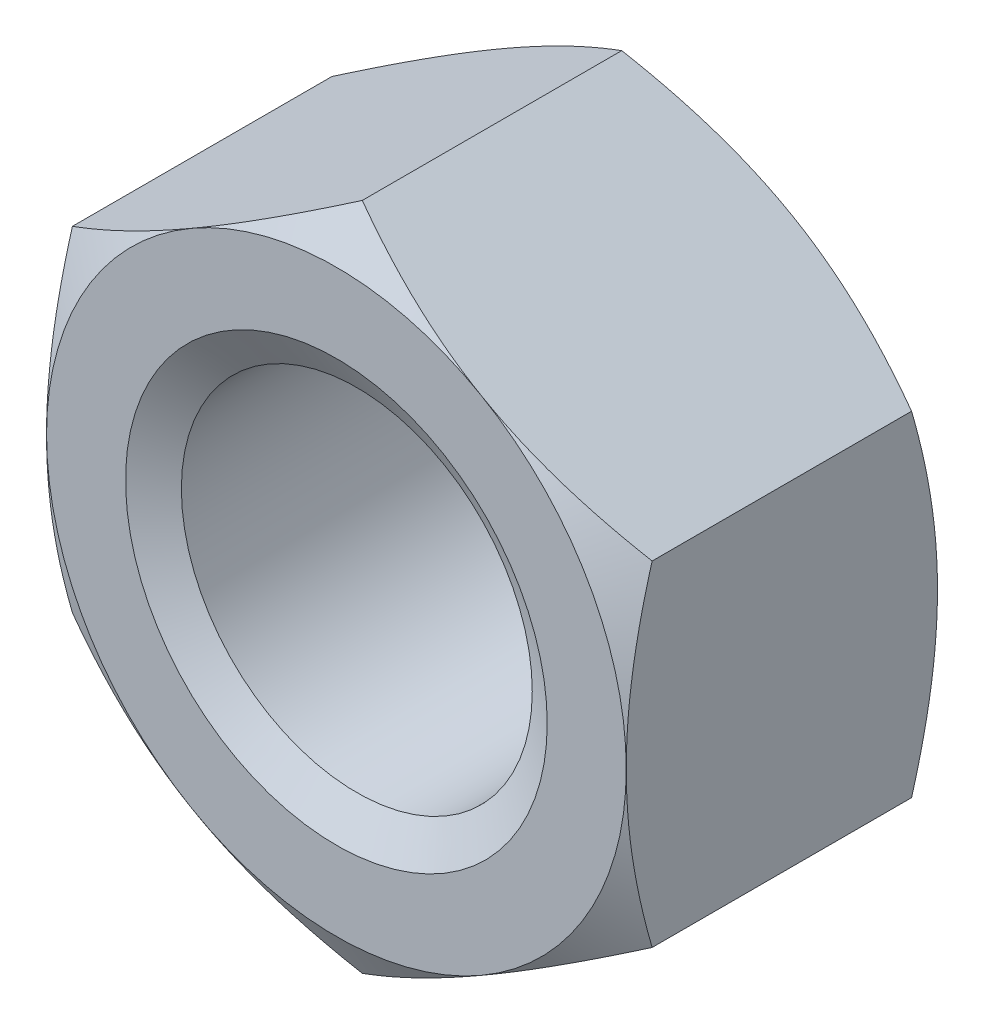
SolidWorks part; units mm, degrees
ref_plane "前视基准面" through (0, 0, 0) normal (0, 0, 1) x (1, 0, 0)
ref_plane "上视基准面" through (0, 0, 0) normal (0, 1, 0) x (1, 0, 0)
ref_plane "右视基准面" through (0, 0, 0) normal (1, 0, 0) x (0, 0, -1)
sketch "草图1" plane through (0, 0, 0) normal (1, 0, 0) x (0, 0, -1)
  line L0 (0, 52.43) -> (0, -52.43) construction
  line L1 (0, 0) -> (51, 0) construction
  line L2 (0, 0) -> (0, 52.43)
  line L3 (0, 52.43) -> (51, 52.43)
  line L4 (51, 52.43) -> (51, 0)
  line L5 (0, 32) -> (51, 32)
  line L6 (0, 28.7525) -> (51, 28.7525)
  line L7 (50, 52.43) -> (50, 0)
  line L8 (0, 47.5) -> (2.8463, 52.43)
  line L9 (0, 32) -> (1.8749, 28.7525)
  line L10 (0, -32) -> (1.8749, -28.7525)
  line L11 (50, 44.1) -> (51, 44.1)
  point P5 (11.7, 0)
  point P10 (45, 0)
  point P22 (0, 69.1)
  dimension "e" = 104.86
  dimension "m" = 51
  dimension "mw" = 39.3
  dimension "D" = 64
  dimension "P" = 6
  dimension "D81" = 57.505
  dimension "c" = 1
  dimension "β" = 30
  dimension "s" = 95
  dimension "θ" = 120
  dimension "dw" = 88.2
  dimension "da" = 69.1
sketch "草图2" plane through (0, 0, 0) normal (0, 0, 1) x (1, 0, 0)
  line L1 (0, 54.8483) -> (-47.5, 27.4241)
  line L2 (-47.5, 27.4241) -> (-47.5, -27.4241)
  line L3 (-47.5, -27.4241) -> (0, -54.8483)
  line L4 (0, -54.8483) -> (47.5, -27.4241)
  line L5 (47.5, -27.4241) -> (47.5, 27.4241)
  line L6 (47.5, 27.4241) -> (0, 54.8483)
  circle A0 centre (0, 0) radius 47.5 construction
  circle A1 centre (0, 0) radius 28.7525
  dimension "D1" = 95
sketch "草图3" plane through (0, 0, 0) normal (0, 0, 1) x (1, 0, 0)
  line L0 (0, 54.8483) -> (-47.5, 27.4241) construction
  line L1 (47.5, 27.4241) -> (0, 54.8483) construction
  line L2 (47.5, -27.4241) -> (47.5, 27.4241) construction
  line L3 (0, -54.8483) -> (47.5, -27.4241) construction
  line L4 (-47.5, -27.4241) -> (0, -54.8483) construction
  line L5 (-47.5, 27.4241) -> (-47.5, -27.4241) construction
  line L6 (0, 54.8483) -> (-47.5, 27.4241)
  line L7 (47.5, 27.4241) -> (0, 54.8483)
  line L8 (47.5, -27.4241) -> (47.5, 27.4241)
  line L9 (0, -54.8483) -> (47.5, -27.4241)
  line L10 (-47.5, -27.4241) -> (0, -54.8483)
  line L11 (-47.5, 27.4241) -> (-47.5, -27.4241)
  circle A0 centre (0, 0) radius 28.7525 construction
  circle A1 centre (0, 0) radius 28.7525
extrude "凸台-拉伸1" add sketch "草图3" against normal up to vertex (51 mm away) up to point (0, 0, -51)
cosmetic thread "装饰螺纹线1" parameters "D2"=64
sketch "草图4" plane through (0, 0, 0) normal (1, 0, 0) x (0, 0, -1)
  line L1 (0, 34.55) -> (3.3472, 28.7525)
  line L2 (0, 0) -> (51, 0) construction
  line L3 (0, 0) -> (51, 0) construction
  line L4 (25.5, 0) -> (25.5, 52.43) construction
  line L5 (0, 52.43) -> (51, 52.43) construction
  line L6 (3.3472, 28.7525) -> (3.3472, 0)
  line L7 (3.3472, 0) -> (0, 0)
  line L8 (0, 0) -> (0, 34.55)
  line L9 (51, 0) -> (51, 34.55)
  line L10 (47.6528, 0) -> (51, 0)
  line L11 (47.6528, 28.7525) -> (47.6528, 0)
  line L12 (51, 34.55) -> (47.6528, 28.7525)
  line L16 (0, 32) -> (1.8749, 28.7525) construction
  line L17 (0, 28.7525) -> (51, 28.7525) construction
  dimension "D1" = 69.1
revolve "切除-旋转1" cut sketch "草图4" angle 360 about L3
sketch "草图5" plane through (0, 0, 0) normal (0, 0, 1) x (1, 0, 0)
  circle A0 centre (0, 0) radius 47.5
  circle A1 centre (0, 0) radius 78.645
  circle A2 centre (0, 0) radius 47.5 construction
  dimension "D1" = 157.29
extrude "切除-拉伸1" cut sketch "草图5" against normal blind 10.2 draft 60
sketch "草图7" plane through (0, 0, -51) normal (0, 0, -1) x (-1, 0, 0)
  circle A1 centre (0, 0) radius 78.645
  circle A2 centre (0, 0) radius 78.645
  circle A3 centre (0, 0) radius 47.5
  circle A4 centre (0, 0) radius 47.5
  dimension "D1" = 0
  dimension "D2" = 0
extrude "切除-拉伸2" cut sketch "草图7" against normal blind 10.2 draft 60
sketch "草图6" [suppressed] plane through (0, 0, 0) normal (1, 0, 0) x (0, 0, -1)
  line L0 (51, 44.1) -> (50, 44.1)
  line L1 (50, 44.1) -> (50, 54.8483)
  line L2 (50, 54.8483) -> (51, 54.8483)
  line L3 (51, 54.8483) -> (51, 44.1)
  line L4 (0, 0) -> (51, 0) construction
  line L5 (0, 0) -> (51, 0) construction
  line L6 (46.7575, 54.8483) -> (4.2425, 54.8483) construction
revolve "切除-旋转2" [suppressed] cut sketch "草图6" angle 360 about L5
equation "\"D81@草图1\" = \"D@草图1\"-1.0825*\"P@草图1\""
equation "\"D1@草图5\" = \"e@草图1\"*1.5"
equation "\"D2@装饰螺纹线1\" = \"D@草图1\""
equation "\"D1@切除-拉伸1\" = \"m@草图1\"/5"
equation "\"D1@切除-拉伸2\" = \"D1@切除-拉伸1\""
equation "\"D1@草图4\" = \"da@草图1\""
equation "\"D1@草图2\" = \"s@草图1\""
